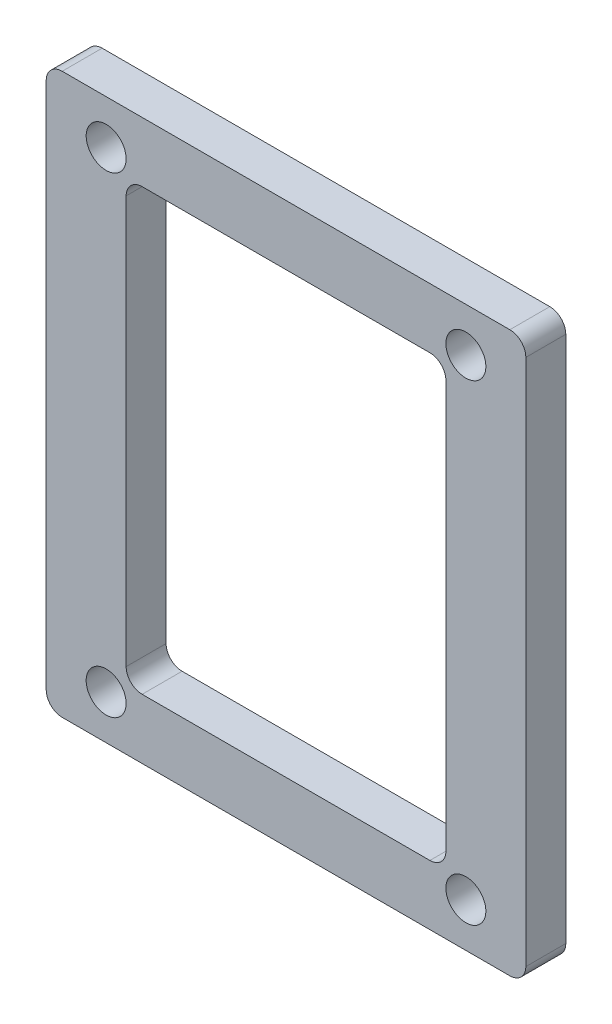
SolidWorks part; units mm, degrees
ref_plane "Plan de face" through (0, 0, 0) normal (0, 0, 1) x (1, 0, 0)
ref_plane "Plan de dessus" through (0, 0, 0) normal (0, 1, 0) x (1, 0, 0)
ref_plane "Plan de droite" through (0, 0, 0) normal (1, 0, 0) x (0, 0, -1)
sketch "Esquisse1" plane through (0, 0, 0) normal (0, 0, 1) x (1, 0, 0)
  line L1 (28, -35) -> (-28, -35)
  line L2 (30, -33) -> (30, 33)
  line L3 (28, 35) -> (-28, 35)
  line L4 (-30, -33) -> (-30, 33)
  line L5 (30, -35) -> (-30, 35) construction
  line L6 (30, 35) -> (-30, -35) construction
  arc A0 (-28, -35) -> (-30, -33) centre (-28, -33) cw
  arc A1 (28, -35) -> (30, -33) centre (28, -33) ccw
  arc A2 (30, 33) -> (28, 35) centre (28, 33) ccw
  arc A3 (-28, 35) -> (-30, 33) centre (-28, 33) ccw
  point P0 (0, 0)
  dimension "D3" = 2
  dimension "D1" = 60
  dimension "D2" = 70
extrude "Boss.-Extru.1" add sketch "Esquisse1" along normal blind 5
sketch "Esquisse2" plane through (0, 0, 0) normal (0, 0, -1) x (-1, 0, 0)
  line L1 (18, -27.5) -> (-18, -27.5)
  line L2 (20, -25.5) -> (20, 25.5)
  line L3 (18, 27.5) -> (-18, 27.5)
  line L4 (-20, -25.5) -> (-20, 25.5)
  line L5 (20, -27.5) -> (-20, 27.5) construction
  line L6 (20, 27.5) -> (-20, -27.5) construction
  arc A0 (-18, -27.5) -> (-20, -25.5) centre (-18, -25.5) cw
  arc A1 (18, -27.5) -> (20, -25.5) centre (18, -25.5) ccw
  arc A2 (20, 25.5) -> (18, 27.5) centre (18, 25.5) ccw
  arc A3 (-18, 27.5) -> (-20, 25.5) centre (-18, 25.5) ccw
  point P0 (0, 0)
  dimension "D3" = 2
  dimension "D1" = 55
  dimension "D2" = 40
extrude "Enlèv. mat.-Extru.1" cut sketch "Esquisse2" against normal through all
sketch "Esquisse3" plane through (0, 0, 5) normal (0, 0, 1) x (1, 0, 0)
  line L0 (28, 35) -> (-28, 35) construction
  line L1 (30, -33) -> (30, 33) construction
  line L2 (-28, -35) -> (28, -35) construction
  line L3 (-30, 33) -> (-30, -33) construction
  circle A4 centre (-22.5, -29.5) radius 2.5
  circle A5 centre (22.5, -29.5) radius 2.5
  circle A6 centre (-22.5, 29.5) radius 2.5
  circle A7 centre (22.5, 29.5) radius 2.5
  dimension "D3" = 5
  dimension "D4" = 5
  dimension "D5" = 5
  dimension "D7" = 5
  dimension "D1" = 5.5
  dimension "D2" = 7.5
  dimension "D6" = 5.5
  dimension "D8" = 7.5
extrude "Enlèv. mat.-Extru.2" cut sketch "Esquisse3" against normal through all
